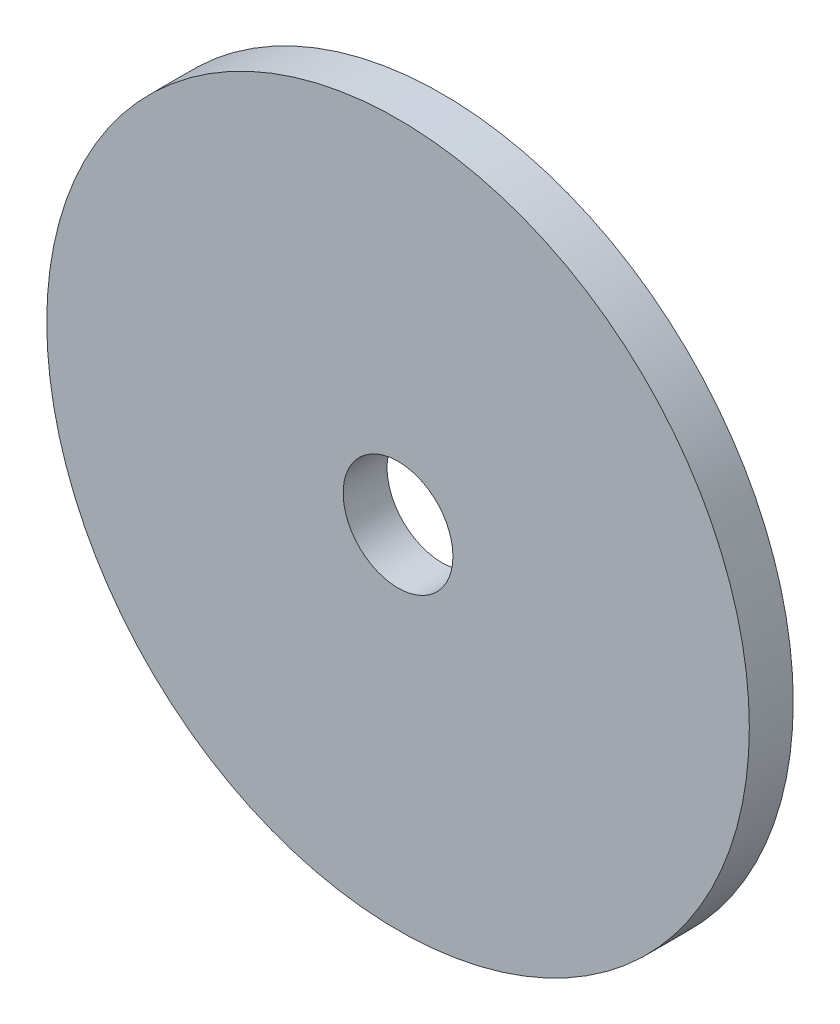
SolidWorks part; units mm, degrees
ref_plane "Front Plane" through (0, 0, 0) normal (0, 0, 1) x (1, 0, 0)
ref_plane "Top Plane" through (0, 0, 0) normal (0, 1, 0) x (1, 0, 0)
ref_plane "Right Plane" through (0, 0, 0) normal (1, 0, 0) x (0, 0, -1)
sketch "Sketch1" plane through (0, 0, 0) normal (0, 0, 1) x (1, 0, 0)
  circle A0 centre (0, 0) radius 120
  circle A1 centre (0, 0) radius 18.75
  dimension "D1" = 240
  dimension "D2" = 37.5
extrude "Boss-Extrude1" add sketch "Sketch1" along normal blind 15
